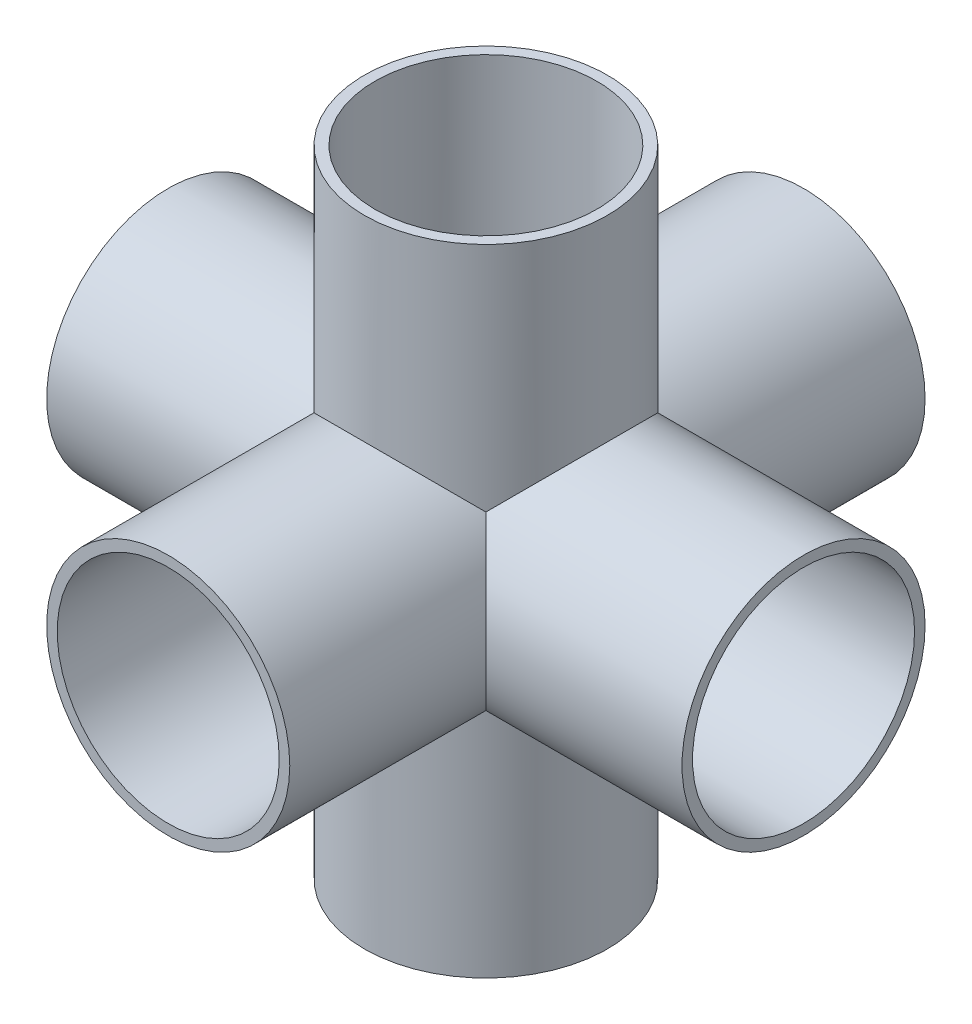
SolidWorks part; units mm, degrees
ref_plane "Front Plane" through (0, 0, 0) normal (0, 0, 1) x (1, 0, 0)
ref_plane "Top Plane" through (0, 0, 0) normal (0, 1, 0) x (1, 0, 0)
ref_plane "Right Plane" through (0, 0, 0) normal (1, 0, 0) x (0, 0, -1)
sketch "Sketch1" plane through (0, 0, 0) normal (0, 1, 0) x (1, 0, 0)
  circle A0 centre (0, 0) radius 19.05
extrude "Extrude1" add sketch "Sketch1" along normal blind 49.784 and the other way blind 49.784
sketch "Sketch2" plane through (0, 0, 0) normal (0, 0, 1) x (1, 0, 0)
  circle A0 centre (0, 0) radius 19.05
extrude "Extrude2" add sketch "Sketch2" along normal blind 49.784 and the other way blind 49.784
sketch "Sketch3" plane through (0, 0, 0) normal (1, 0, 0) x (0, 0, -1)
  circle A0 centre (0, 0) radius 19.05
extrude "Extrude3" add sketch "Sketch3" along normal blind 49.784 and the other way blind 49.784
sketch "Sketch4" plane through (0, 0, 0) normal (0, 1, 0) x (1, 0, 0)
  circle A0 centre (0, 0) radius 17.399
  dimension "D1" = 34.798
extrude "Cut-Extrude1" cut sketch "Sketch4" against normal through all and the other way through all
sketch "Sketch5" plane through (0, 0, 0) normal (1, 0, 0) x (0, 0, -1)
  circle A0 centre (0, 0) radius 17.399
  dimension "D1" = 34.798
extrude "Cut-Extrude2" cut sketch "Sketch5" against normal through all and the other way through all
sketch "Sketch6" plane through (0, 0, 0) normal (0, 0, 1) x (1, 0, 0)
  circle A0 centre (0, 0) radius 17.399
  dimension "D1" = 34.798
extrude "Cut-Extrude3" cut sketch "Sketch6" against normal through all and the other way through all
sketch "Sketch7" plane through (0, 0, 0) normal (0, 1, 0) x (1, 0, 0)
  line L0 (0, 0) -> (0, 7.2437)
sketch "Sketch8" plane through (0, 0, 0) normal (0, 0, 1) x (1, 0, 0)
  line L0 (0, 0) -> (-5.0486, 0)
sketch "Sketch9" plane through (0, 0, 0) normal (1, 0, 0) x (0, 0, -1)
  line L0 (0, 0) -> (0, 5.8169)
